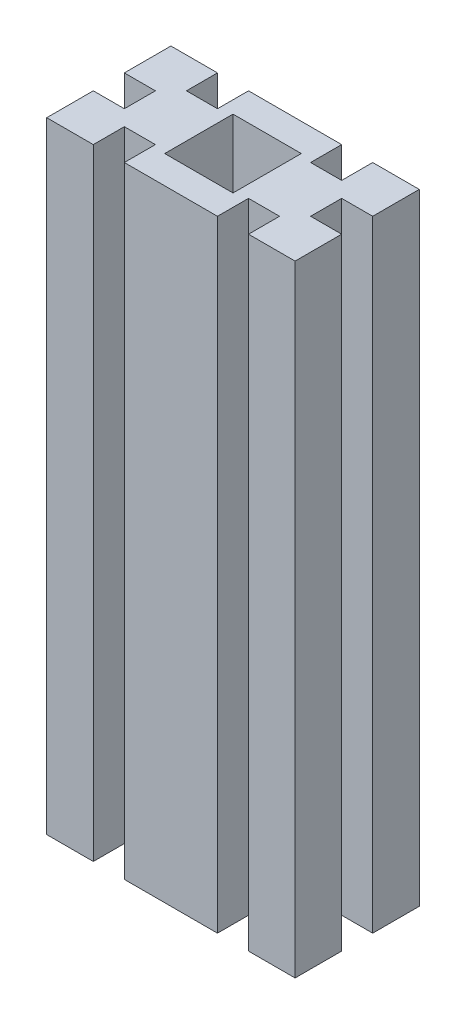
SolidWorks part; units mm, degrees
ref_plane "Front Plane" through (0, 0, 0) normal (0, 0, 1) x (1, 0, 0)
ref_plane "Top Plane" through (0, 0, 0) normal (0, 1, 0) x (1, 0, 0)
ref_plane "Right Plane" through (0, 0, 0) normal (1, 0, 0) x (0, 0, -1)
sketch "Sketch1" plane through (0, 0, 0) normal (0, 1, 0) x (1, 0, 0)
  line L1 (20, -10) -> (-20, -10)
  line L2 (20, -10) -> (20, 10)
  line L3 (20, 10) -> (-20, 10)
  line L4 (-20, -10) -> (-20, 10)
  line L5 (20, -10) -> (-20, 10) construction
  line L6 (20, 10) -> (-20, -10) construction
  point P0 (0, 0)
  dimension "D1" = 20
  dimension "D2" = 40
extrude "Body" add sketch "Sketch1" along normal blind 100
sketch "Sketch2" plane through (0, 100, 0) normal (0, 1, 0) x (1, 0, 0)
  line L0 (20, 10) -> (-20, 10) construction
  line L1 (-12.5, 10) -> (-7.5, 10)
  line L2 (-12.5, 10) -> (-12.5, 5)
  line L3 (-12.5, 5) -> (-7.5, 5)
  line L4 (-7.5, 10) -> (-7.5, 5)
  line L5 (-20, 10) -> (-20, -10) construction
  line L6 (-20, 2.5) -> (-15, 2.5)
  line L7 (-20, 2.5) -> (-20, -2.5)
  line L8 (-20, -2.5) -> (-15, -2.5)
  line L9 (-15, 2.5) -> (-15, -2.5)
  line L10 (-20, -10) -> (20, -10) construction
  line L11 (-12.5, -10) -> (-7.5, -10)
  line L12 (-12.5, -10) -> (-12.5, -5)
  line L13 (-12.5, -5) -> (-7.5, -5)
  line L14 (-7.5, -10) -> (-7.5, -5)
  line L15 (0, -1000) -> (0, 49000) construction
  line L16 (7.5, -10) -> (7.5, -5)
  line L17 (12.5, -5) -> (7.5, -5)
  line L18 (12.5, -10) -> (12.5, -5)
  line L19 (12.5, -10) -> (7.5, -10)
  line L20 (15, 2.5) -> (15, -2.5)
  line L21 (20, -2.5) -> (15, -2.5)
  line L22 (20, 2.5) -> (20, -2.5)
  line L23 (20, 2.5) -> (15, 2.5)
  line L24 (7.5, 10) -> (7.5, 5)
  line L25 (12.5, 5) -> (7.5, 5)
  line L26 (12.5, 10) -> (12.5, 5)
  line L27 (12.5, 10) -> (7.5, 10)
  line L29 (5.5, 5.5) -> (-5.5, 5.5)
  line L30 (5.5, 5.5) -> (5.5, -5.5)
  line L31 (5.5, -5.5) -> (-5.5, -5.5)
  line L32 (-5.5, 5.5) -> (-5.5, -5.5)
  line L33 (5.5, 5.5) -> (-5.5, -5.5) construction
  line L34 (5.5, -5.5) -> (-5.5, 5.5) construction
  point P18 (-15, 0)
  point P35 (0, 0)
  dimension "D1" = 5
  dimension "D2" = 5
  dimension "D3" = 7.5
  dimension "D4" = 11
extrude "Profilage" cut sketch "Sketch2" against normal through all
